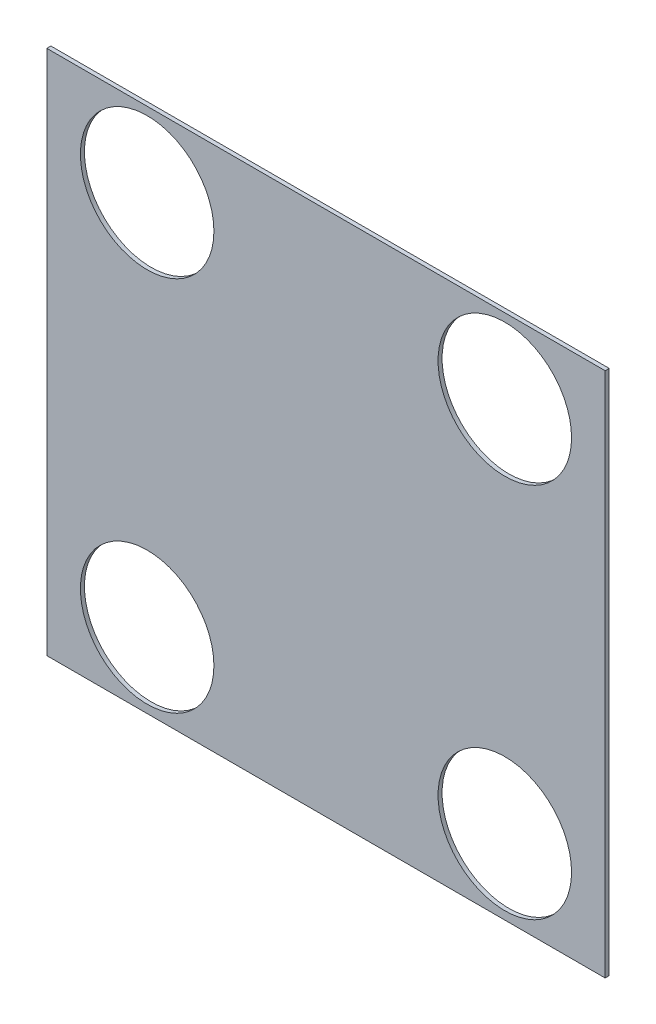
SolidWorks part; units mm, degrees
ref_plane "前视基准面" through (0, 0, 0) normal (0, 0, 1) x (1, 0, 0)
ref_plane "上视基准面" through (0, 0, 0) normal (0, 1, 0) x (1, 0, 0)
ref_plane "右视基准面" through (0, 0, 0) normal (1, 0, 0) x (0, 0, -1)
other "Configuration Table"
sketch "草图1" plane through (0, 0, 0) normal (0, 0, 1) x (1, 0, 0)
  line L0 (0, 0) -> (690, 0)
  line L1 (690, 0) -> (690, 650)
  line L2 (690, 650) -> (0, 650)
  line L3 (0, 650) -> (0, 0)
  dimension "width" = 690
  dimension "height" = 650
extrude "Bottom_plate" add sketch "草图1" along normal blind 5
sketch "草图2" plane through (0, 0, 5) normal (0, 0, 1) x (1, 0, 0)
  circle A0 centre (124, 92.5) radius 82.5
  dimension "diameter" = 165
  dimension "x" = 124
  dimension "y" = 92.5
extrude "Grab_clearance" cut sketch "草图2" against normal through all
sketch "草图3" plane through (0, 0, 5) normal (0, 0, 1) x (1, 0, 0)
  circle A0 centre (124, 557.5) radius 82.5
  dimension "diameter" = 165
  dimension "x" = 124
  dimension "y" = 557.5
extrude "切除-拉伸2" cut sketch "草图3" against normal through all
sketch "草图4" plane through (0, 0, 5) normal (0, 0, 1) x (1, 0, 0)
  circle A0 centre (566, 92.5) radius 82.5
  dimension "diameter" = 165
  dimension "x" = 566
  dimension "y" = 92.5
extrude "切除-拉伸3" cut sketch "草图4" against normal through all
sketch "草图5" plane through (0, 0, 5) normal (0, 0, 1) x (1, 0, 0)
  circle A0 centre (566, 557.5) radius 82.5
  dimension "diameter" = 165
  dimension "x" = 566
  dimension "y" = 557.5
extrude "切除-拉伸4" cut sketch "草图5" against normal through all
